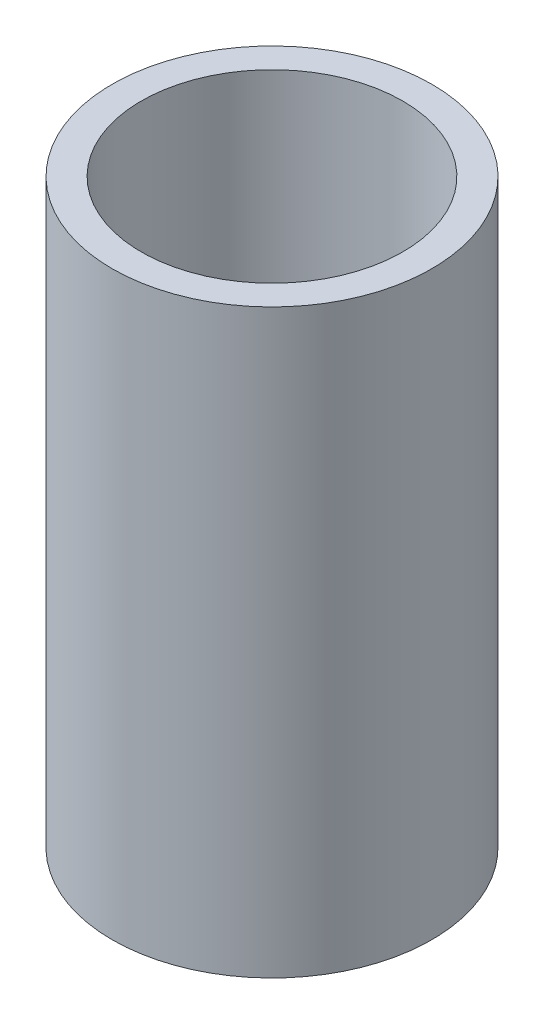
SolidWorks part; units mm, degrees
ref_plane "Спереди" through (0, 0, 0) normal (0, 0, 1) x (1, 0, 0)
ref_plane "Сверху" through (0, 0, 0) normal (0, 1, 0) x (1, 0, 0)
ref_plane "Справа" through (0, 0, 0) normal (1, 0, 0) x (0, 0, -1)
sketch "Эскиз1" plane through (0, 0, 0) normal (0, 0, 1) x (1, 0, 0)
  line L0 (0, -110.6031) -> (0, 130.0787) construction
  line L1 (45, 100) -> (55, 100)
  line L2 (45, 100) -> (45, -100)
  line L3 (45, -100) -> (55, -100)
  line L4 (55, 100) -> (55, -100)
  point P4 (45, 0)
  dimension "D1" = 10
  dimension "D2" = 200
  dimension "D3" = 45
revolve "Повернуть1" add sketch "Эскиз1" angle 360 about L0
